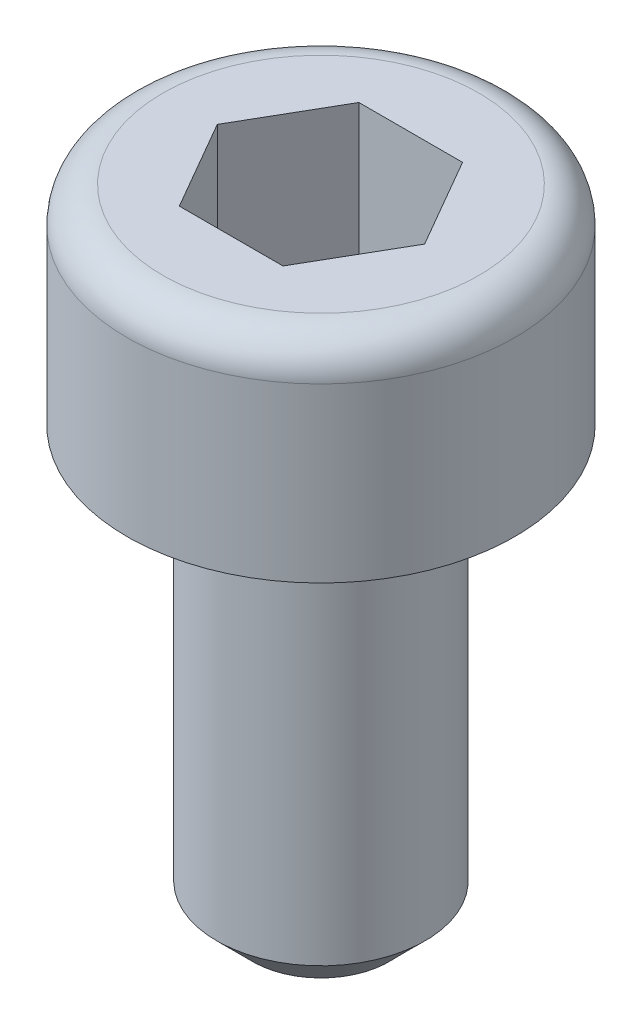
SolidWorks part; units mm, degrees
material "1023 Tôle d'acier au carbone (SS)"
ref_plane "Plan de face" through (0, 0, 0) normal (0, 0, 1) x (1, 0, 0)
ref_plane "Plan de dessus" through (0, 0, 0) normal (0, 1, 0) x (1, 0, 0)
ref_plane "Plan de droite" through (0, 0, 0) normal (1, 0, 0) x (0, 0, -1)
sketch "Esquisse1" plane through (0, 0, 0) normal (0, 0, 1) x (1, 0, 0)
  line L0 (0, 15.8257) -> (0, -15.8257) construction
  line L1 (0, 2.9) -> (-2.2, 2.9)
  line L2 (-2.7, 2.4) -> (-2.7, 0)
  line L3 (-2.7, 0) -> (-1.45, 0)
  line L4 (-1.45, 0) -> (-1.45, -5.5)
  line L5 (-1.45, -5.5) -> (-0.95, -6)
  line L6 (-0.95, -6) -> (0, -6)
  line L7 (0, 2.9) -> (0, -6)
  arc A0 (-2.2, 2.9) -> (-2.7, 2.4) centre (-2.2, 2.4) ccw
  point P11 (-1.45, -6)
  dimension "D5" = 0.5
  dimension "D1" = 5.4
  dimension "D3" = 6
  dimension "D4" = 2.9
  dimension "D8" = 0.5
  dimension "D6" = 2.9
revolve "Révolution1" add sketch "Esquisse1" angle 360 about L0
cosmetic thread "Représentation de filetage1" parameters "D2"=2.3
sketch "Esquisse2" plane through (0, 2.9, 0) normal (0, 1, 0) x (-1, 0, 0)
  line L1 (-1.4434, 0) -> (-0.7217, -1.25)
  line L2 (-0.7217, -1.25) -> (0.7217, -1.25)
  line L3 (0.7217, -1.25) -> (1.4434, 0)
  line L4 (1.4434, 0) -> (0.7217, 1.25)
  line L5 (0.7217, 1.25) -> (-0.7217, 1.25)
  line L6 (-0.7217, 1.25) -> (-1.4434, 0)
  circle A0 centre (0, 0) radius 1.25 construction
  dimension "D1" = 2.5
extrude "Enlèv. mat.-Extru.1" cut sketch "Esquisse2" against normal blind 2
